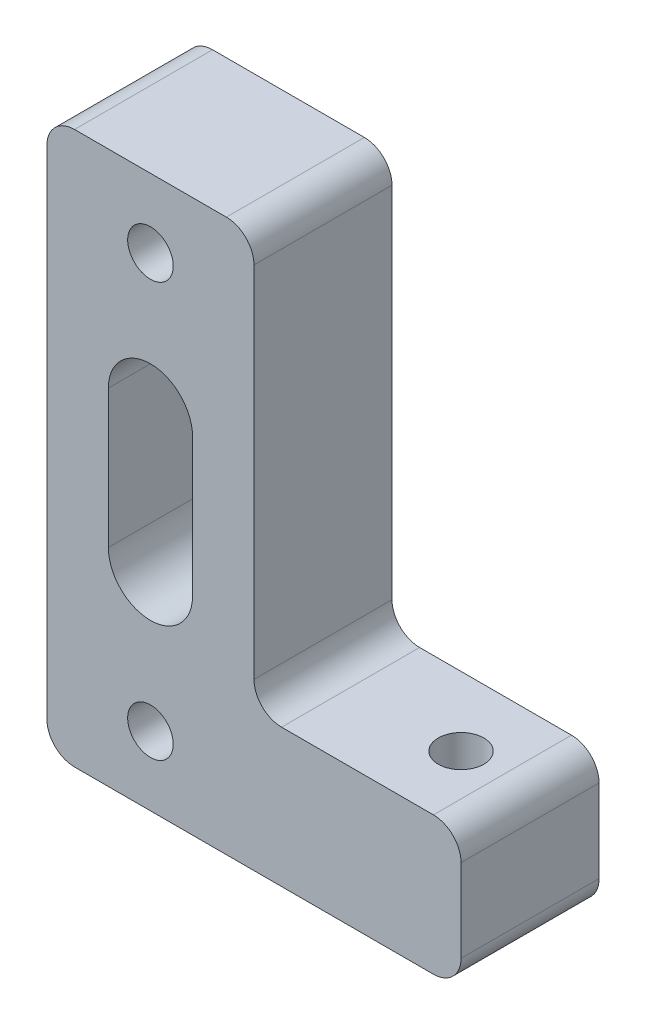
SolidWorks part; units mm, degrees
material "5052-H34"
ref_plane "正面" through (0, 0, 0) normal (0, 0, 1) x (1, 0, 0)
ref_plane "平面" through (0, 0, 0) normal (0, 1, 0) x (1, 0, 0)
ref_plane "右側面" through (0, 0, 0) normal (1, 0, 0) x (0, 0, -1)
sketch "ｽｹｯﾁ1" plane through (0, 0, 0) normal (0, 0, 1) x (1, 0, 0)
  line L0 (0, 0) -> (0, -40)
  line L1 (0, -40) -> (30, -40)
  line L2 (30, -40) -> (30, -30)
  line L3 (30, -30) -> (15, -30)
  line L4 (15, -30) -> (15, 0)
  line L5 (15, 0) -> (0, 0)
  line L6 (7.5, 0) -> (7.5, -40) construction
  circle A0 centre (7.5, -5) radius 1.65
  circle A1 centre (7.5, -35) radius 1.65
  point P11 (7.5, -34.7684)
  dimension "D4" = 3.3
  dimension "D5" = 5
  dimension "D6" = 5
  dimension "D1" = 15
  dimension "D2" = 40
  dimension "D3" = 30
  dimension "D7" = 10
extrude "ﾎﾞｽ - 押し出し1" add sketch "ｽｹｯﾁ1" along normal blind 10
sketch "ｽｹｯﾁ5" plane through (0, -40, 0) normal (0, -1, 0) x (1, 0, 0)
  line L0 (30, 5) -> (0, 5) construction
  line L1 (30, 10) -> (30, 0) construction
  line L2 (0, 10) -> (0, 0) construction
  circle A0 centre (25, 5) radius 1.65
  dimension "D1" = 3.3
  dimension "D2" = 5
extrude "ｶｯﾄ - 押し出し2" cut sketch "ｽｹｯﾁ5" against normal up to surface (10 mm away) up to face at (22.5, -30, 5)
sketch "ｽｹｯﾁ7" plane through (0, 0, 10) normal (0, 0, 1) x (1, 0, 0)
  line L0 (7.5, 0) -> (7.5, -40) construction
  line L1 (15, 0) -> (0, 0) construction
  line L2 (0, -40) -> (30, -40) construction
  line L3 (30, -35) -> (0, -35) construction
  line L4 (30, -40) -> (30, -30) construction
  line L5 (0, 0) -> (0, -40) construction
  line L6 (7.5, -15) -> (7.5, -25) construction
  line L7 (10.55, -15) -> (10.55, -25)
  line L8 (4.45, -15) -> (4.45, -25)
  arc A0 (10.55, -15) -> (4.45, -15) centre (7.5, -15) ccw
  arc A1 (4.45, -25) -> (10.55, -25) centre (7.5, -25) ccw
  point P14 (7.5, -20)
  dimension "D1" = 3.05
  dimension "D3" = 15
  dimension "D2" = 15
extrude "body cut" cut sketch "ｽｹｯﾁ7" against normal up to surface (10 mm away) up to face at (15, -23.3333, 0)
fillet "ﾌｨﾚｯﾄ1" radius 2 1 edges at (15, -30, 5)
fillet "ﾌｨﾚｯﾄ2" radius 2 5 edges at (0, 0, 5) (15, 0, 5) (30, -30, 5) (30, -40, 5) (0, -40, 5)
